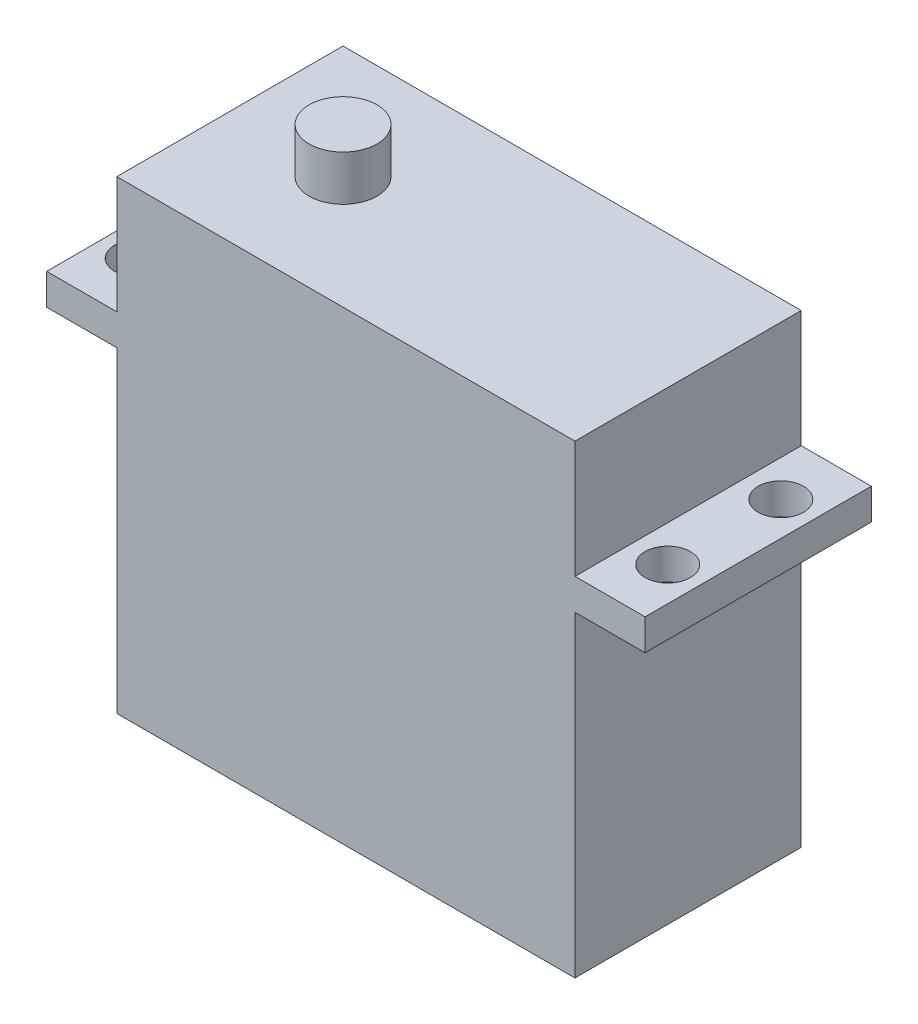
SolidWorks part; units mm, degrees
ref_plane "前视基准面" through (0, 0, 0) normal (0, 0, 1) x (1, 0, 0)
ref_plane "上视基准面" through (0, 0, 0) normal (0, 1, 0) x (1, 0, 0)
ref_plane "右视基准面" through (0, 0, 0) normal (1, 0, 0) x (0, 0, -1)
sketch "草图1" plane through (0, 0, 0) normal (0, 0, 1) x (1, 0, 0)
  line L1 (20.25, -20.55) -> (-20.25, -20.55)
  line L2 (20.25, -20.55) -> (20.25, 20.55)
  line L3 (20.25, 20.55) -> (-20.25, 20.55)
  line L4 (-20.25, -20.55) -> (-20.25, 20.55)
  line L5 (20.25, -20.55) -> (-20.25, 20.55) construction
  line L6 (20.25, 20.55) -> (-20.25, -20.55) construction
  point P0 (0, 0)
  dimension "D1" = 40.5
  dimension "D2" = 41.1
extrude "凸台-拉伸1" add sketch "草图1" against normal blind 20
sketch "草图2" plane through (20.25, 0, 0) normal (1, 0, 0) x (0, 0, -1)
  line L0 (0, 7.45) -> (20, 7.45)
  line L1 (0, -20.55) -> (0, 20.55) construction
  line L2 (20, -20.55) -> (20, 20.55) construction
  line L3 (20, -20.55) -> (0, -20.55) construction
  line L4 (0, 10.2) -> (20, 10.2)
  line L5 (0, 10.2) -> (0, 7.45)
  line L6 (20, 10.2) -> (20, 7.45)
  dimension "D1" = 28
  dimension "D2" = 2.75
extrude "凸台-拉伸2" add sketch "草图2" along normal blind 6.2
sketch "草图3" plane through (0, 10.2, 0) normal (0, 1, 0) x (1, 0, 0)
  line L0 (-23.1968, 10) -> (36.4286, 10) construction
  line L1 (26.45, 20) -> (26.45, 0) construction
  circle A0 centre (23.45, 5) radius 2
  circle A1 centre (23.45, 15) radius 2
  point P4 (26.45, 10)
  point P9 (25.8809, -0.7644)
  dimension "D1" = 4
  dimension "D2" = 5
  dimension "D3" = 3
extrude "切除-拉伸1" cut sketch "草图3" against normal blind 6.2
mirror "镜向2" about plane through (0, 0, 0) normal (1, 0, 0) of "切除-拉伸1", "凸台-拉伸2"
sketch "草图4" plane through (0, 20.55, 0) normal (0, 1, 0) x (1, 0, 0)
  line L0 (-23.2412, 10) -> (29.2671, 10) construction
  line L1 (-20.25, 20) -> (-20.25, 0) construction
  circle A0 centre (-10.25, 10) radius 3
  point P4 (-20.25, 10)
  dimension "D1" = 10
  dimension "D2" = 6
extrude "凸台-拉伸3" add sketch "草图4" along normal blind 4
